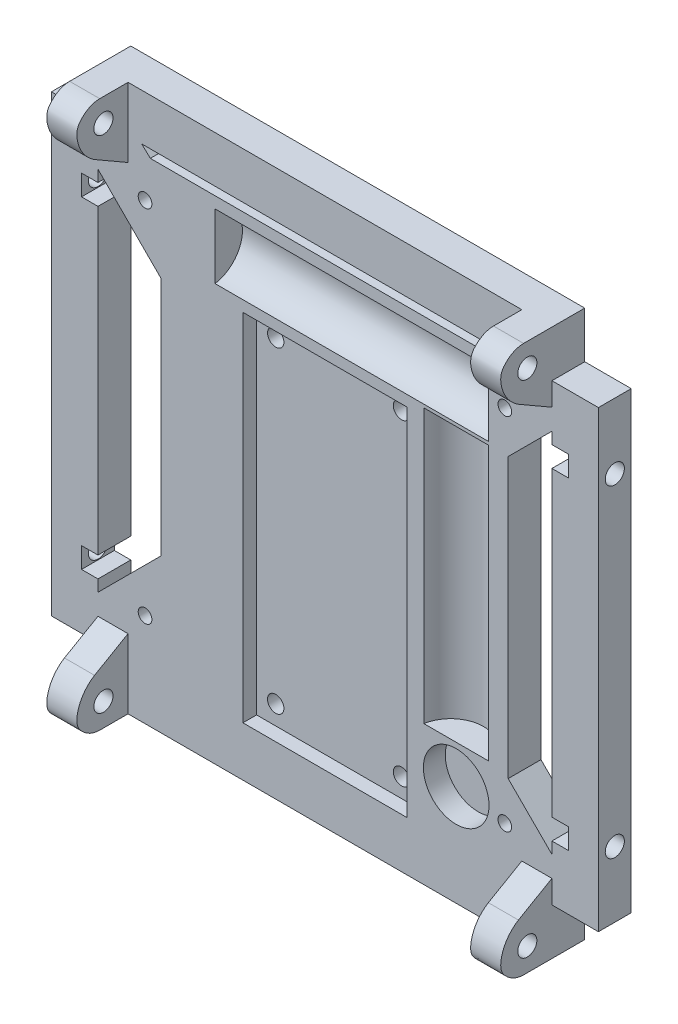
SolidWorks part; units mm, degrees
ref_plane "Front Plane" through (0, 0, 0) normal (0, 0, 1) x (1, 0, 0)
ref_plane "Top Plane" through (0, 0, 0) normal (0, 1, 0) x (1, 0, 0)
ref_plane "Right Plane" through (0, 0, 0) normal (1, 0, 0) x (0, 0, -1)
sketch "Sketch1" plane through (0, 0, 0) normal (0, 0, 1) x (1, 0, 0)
  line L0 (41.5, 50) -> (41.5, 41.5)
  line L1 (-41.5, 50) -> (41.5, 50)
  line L2 (-50, 41.5) -> (-50, -41.5)
  line L3 (-41.5, -50) -> (41.5, -50)
  line L4 (50, 41.5) -> (50, -41.5)
  line L5 (-41.6681, 41.6681) -> (-41.5, 41.5) construction
  line L7 (41.5, 41.5) -> (50, 41.5)
  line L8 (-50, -41.5) -> (-41.5, -41.5)
  line L9 (-41.5, -41.5) -> (-41.5, -50)
  line L10 (0, -55) -> (0, 55) construction
  line L11 (41.5, -41.5) -> (41.5, -50)
  line L12 (50, -41.5) -> (41.5, -41.5)
  line L13 (-50, 41.5) -> (-41.5, 41.5)
  line L15 (-41.5, 50) -> (-41.5, 41.5)
  line L16 (-41.5, 41.5) -> (-50, 41.5)
  point P0 (0, 0)
  dimension "D3" = 8.5
extrude "Boss-Extrude1" add sketch "Sketch1" along normal blind 6 contours L1 L15 L13 L2 L8 L9 L3 L11 L12 L4 L7 L0
sketch "Sketch2" plane through (0, 0, 6) normal (0, 0, 1) x (1, 0, 0)
  line L0 (-41.5, 33.5) -> (-41.5, -33.5)
  line L2 (41.5, -41.5) -> (41.5, 41.5)
  line L3 (41.5, 41.5) -> (-41.5, 41.5)
  line L4 (-30, 22) -> (-30, -22)
  line L9 (-20, 20) -> (20, -20) construction
  line L10 (-20, -20) -> (20, 20) construction
  line L11 (-41.5, 33.5) -> (-30, 22)
  line L12 (-41.5, -33.5) -> (-30, -22)
  line L13 (0, -3.3) -> (0, 3.3) construction
  line L14 (41.5, 33.5) -> (33.5, 25.5)
  line L15 (41.5, 33.5) -> (41.5, -33.5)
  line L16 (41.5, -33.5) -> (33.5, -25.5)
  line L23 (33.5, 41.5) -> (-33.5, 41.5)
  line L24 (-33.5, 41.5) -> (-31.9265, 39.9949)
  line L26 (33.5, 41.5) -> (31.9265, 39.9949)
  line L27 (33.5, 25.5) -> (33.5, -25.5)
  line L28 (-20, 20) -> (20, 20)
  line L29 (-20, 20) -> (-20, -20)
  line L30 (-20, -20) -> (20, -20)
  line L31 (20, 20) -> (20, -20)
  line L32 (-20, 20) -> (20, -20) construction
  line L33 (-20, -20) -> (20, 20) construction
  line L35 (31.9265, 39.9949) -> (-31.9265, 39.9949)
  point P8 (0, 0)
  point P36 (0, 0)
  dimension "D3" = 8
  dimension "D4" = 19.5
  dimension "D5" = 8
  dimension "D6" = 19.5
  dimension "D7" = 40
extrude "Cut-Extrude1" cut sketch "Sketch2" against normal blind 6
ref_plane "Plane1" through (41.5, 0, 0) normal (1, 0, 0) x (0, 0, -1)
sketch "Sketch3" plane through (41.5, 0, 0) normal (1, 0, 0) x (0, 0, -1)
  line L0 (-6, 41.5) -> (-6, 37.3)
  line L1 (-6, 41.5) -> (-6, -41.5) construction
  line L2 (-6, 37.3) -> (-12.1228, 40.835)
  line L3 (-6, 50) -> (-11.1789, 50)
  line L4 (-11.1789, 50) -> (-12.1228, 40.835)
  line L5 (-11.6509, 45.4175) -> (-11.6509, 49.9675)
  line L6 (-11.6509, 45.4175) -> (-12.1175, 49.8875)
  line L7 (-11.6509, 45.4175) -> (-14.21, 48.7575)
  line L8 (-11.6509, 45.4175) -> (-15.1209, 47.5875)
  line L9 (-11.6509, 45.4175) -> (-15.1809, 45.0421)
  line L10 (-11.6509, 45.4175) -> (-13.7488, 42.243)
  line L11 (-6, 50) -> (-6, 37.3)
  circle A0 centre (-10.5, 45.75) radius 1.75
  spline S0 degree 3 poles (-11.1789, 50) (-11.4938, 49.9924) (-12.6052, 49.8729) (-14.0499, 49.0428) (-15.4987, 47.3648) (-15.2595, 43.9691) (-13.6433, 41.7946) (-12.1228, 40.835) knots 0 0 0 0 0.074833 0.262848 0.380075 0.581369 1 1 1 1
  point P9 (-10.5, 45.75)
  dimension "D7" = 11.84
  dimension "D1" = 4.2
  dimension "D2" = 60
  dimension "D3" = 7.07
  dimension "D4" = 5.88
  dimension "D5" = 4.25
  dimension "D6" = 4.5
  dimension "D8" = 43.34
  dimension "D9" = 63.86
  dimension "D10" = 101.95
  dimension "D11" = 152.42
  dimension "D12" = 4.55
  dimension "D13" = 4.47
  dimension "D14" = 3.34
  dimension "D15" = 2.17
  dimension "D16" = 3.53
  dimension "D17" = 3.1745
extrude "Boss-Extrude2" add sketch "Sketch3" against normal blind 5.5 contours A0 L4 L2 L0 L11 L3 | L10 S0 L4 A0 | L9 S0 L10 A0 | L8 S0 L9 A0 | L7 S0 L8 A0 | L6 S0 L7 A0 | L5 S0 L6 A0 | L4 S0 L5 A0
mirror "Mirror1" about plane through (0, 0, 0) normal (1, 0, 0) of "Boss-Extrude2"
mirror "Mirror2" about plane through (0, 0, 0) normal (0, 1, 0) of "Mirror1", "Boss-Extrude2"
sketch "Sketch4" plane through (0, 0, 0) normal (0, 0, 1) x (1, 0, 0)
  circle A0 centre (32.89, 32.89) radius 1.25
  point P0 (32.89, 32.89)
  dimension "D1" = 8.61
  dimension "D2" = 8.61
extrude "Cut-Extrude2" cut sketch "Sketch4" along normal through all
mirror "Mirror3" about plane through (0, 0, 0) normal (0, 1, 0) of "Cut-Extrude2"
mirror "Mirror4" about plane through (0, 0, 0) normal (1, 0, 0) of "Mirror3", "Cut-Extrude2"
ref_plane "Plane2" through (-50, 0, 0) normal (-1, 0, 0) x (0, 0, 1)
sketch "Sketch5" plane through (-50, 0, 0) normal (-1, 0, 0) x (0, 0, 1)
  circle A0 centre (3, 29.5) radius 1.75
  point P0 (3, 29.5)
  dimension "D1" = 3
  dimension "D2" = 20.5
extrude "Cut-Extrude3" cut sketch "Sketch5" against normal blind 5.5
ref_plane "Plane3" through (-41.5, 0, 0) normal (-1, 0, 0) x (0, 0, 1)
sketch "Sketch7" plane through (0, 0, 0) normal (0, 0, 1) x (1, 0, 0)
  line L0 (-41.5, 3.3) -> (-41.5, -3.3) construction
  line L1 (-41.5, 31.38) -> (-44.5, 31.38)
  line L2 (-41.5, 31.38) -> (-41.5, 27.61)
  line L3 (-41.5, 27.61) -> (-44.5, 27.61)
  line L4 (-44.5, 31.38) -> (-44.5, 27.61)
  line L5 (-41.5, 33.5) -> (-30, 22) construction
  point P6 (-41.5, 33.5)
  dimension "D1" = 3
  dimension "D2" = 3.77
  dimension "D3" = 2.12
extrude "Cut-Extrude4" cut sketch "Sketch7" along normal up to next
mirror "Mirror7" about plane through (0, 0, 0) normal (0, 1, 0) of "Cut-Extrude4"
mirror "Mirror8" about plane through (0, 0, 0) normal (1, 0, 0) of "Mirror7", "Cut-Extrude4"
mirror "Mirror11" about plane through (0, 0, 0) normal (1, 0, 0) of "Cut-Extrude3"
mirror "Mirror12" about plane through (0, 0, 0) normal (0, 1, 0) of "Mirror11", "Cut-Extrude3"
ref_plane "Plane4" through (29.92, 0, 0) normal (1, 0, 0) x (0, 0, -1)
sketch "Sketch9" plane through (29.92, 0, 0) normal (1, 0, 0) x (0, 0, -1)
  line L1 (-6, 41.5) -> (-6, -41.5) construction
  line L3 (0, 41.5) -> (0, -41.5) construction
  line L5 (-6, 37.9161) -> (-6, 26.0839)
  arc A1 (-6, 26.0839) -> (-6, 37.9161) centre (-7, 32) ccw
  point P6 (-7, 32)
  dimension "D4" = 7
ref_plane "Plane5" through (0, 25.5, 0) normal (0, 1, 0) x (1, 0, 0)
sketch "Sketch11" plane through (0, 25.5, 0) normal (0, 1, 0) x (1, 0, 0)
  line L4 (50, -6) -> (50, 0) construction
  line L5 (-41.5, 0) -> (41.5, 0) construction
  line L6 (18.0839, -6) -> (29.9161, -6)
  line L7 (-36, -6) -> (36, -6) construction
  arc A1 (29.9161, -6) -> (18.0839, -6) centre (24, -7) ccw
  point P0 (24, -7)
  dimension "D2" = 7
  dimension "D3" = 6
  dimension "D1" = 26
extrude "Cut-Extrude7" cut sketch "Sketch11" against normal blind 50
extrude "Cut-Extrude8" cut sketch "Sketch9" against normal blind 50
sketch "Sketch14" plane through (0, 0, 6) normal (0, 0, 1) x (1, 0, 0)
  line L0 (29.9161, -24.5) -> (18.0839, -24.5) construction
  circle A0 centre (24, -31.5) radius 6
  point P0 (24, -31.5)
  dimension "D1" = 7
extrude "Cut-Extrude9" cut sketch "Sketch14" against normal blind 4
sketch "Sketch15" plane through (0, 0, 6) normal (0, 0, 1) x (1, 0, 0)
  line L0 (-20.08, 26.0839) -> (29.92, 26.0839) construction
  line L1 (-15, 24.0839) -> (15, 24.0839)
  line L2 (-15, 24.0839) -> (-15, -40.9161)
  line L3 (-15, -40.9161) -> (15, -40.9161)
  line L4 (15, 24.0839) -> (15, -40.9161)
  line L5 (-50, 41.5) -> (-50, -41.5) construction
  dimension "D1" = 30
  dimension "D2" = 65
  dimension "D3" = 2
  dimension "D4" = 35
extrude "Cut-Extrude10" cut sketch "Sketch15" against normal blind 2.5
sketch "Sketch16" plane through (0, 0, 6) normal (0, 0, 1) x (1, 0, 0)
  line L0 (47, 17.3695) -> (47, -39.2157)
  line L1 (50, 41.5) -> (50, -41.5) construction
  line L2 (-36, -50) -> (36, -50) construction
  point P4 (24, -31.5)
  dimension "D1" = 3
  dimension "D2" = 26
  dimension "D3" = 18.5
sketch "Sketch17" plane through (0, 0, 3.5) normal (0, 0, 1) x (1, 0, 0)
  line L0 (-15, 24.0839) -> (-15, -40.9161) construction
  line L1 (-15, -40.9161) -> (15, -40.9161) construction
  line L2 (0, -40.9161) -> (0, -37.4061)
  line L3 (-15, -8.4161) -> (-22.1851, -8.4161)
  circle A0 centre (-11.5, -37.4061) radius 1.5
  circle A1 centre (11.5, -37.4061) radius 1.5
  circle A2 centre (-11.5, 20.5739) radius 1.5
  circle A3 centre (11.5, 20.5739) radius 1.5
  dimension "D1" = 3
  dimension "D2" = 3.5
  dimension "D3" = 3.51
extrude "Cut-Extrude11" cut sketch "Sketch17" against normal blind 5 contours A2 | A3 | A0 | A1
